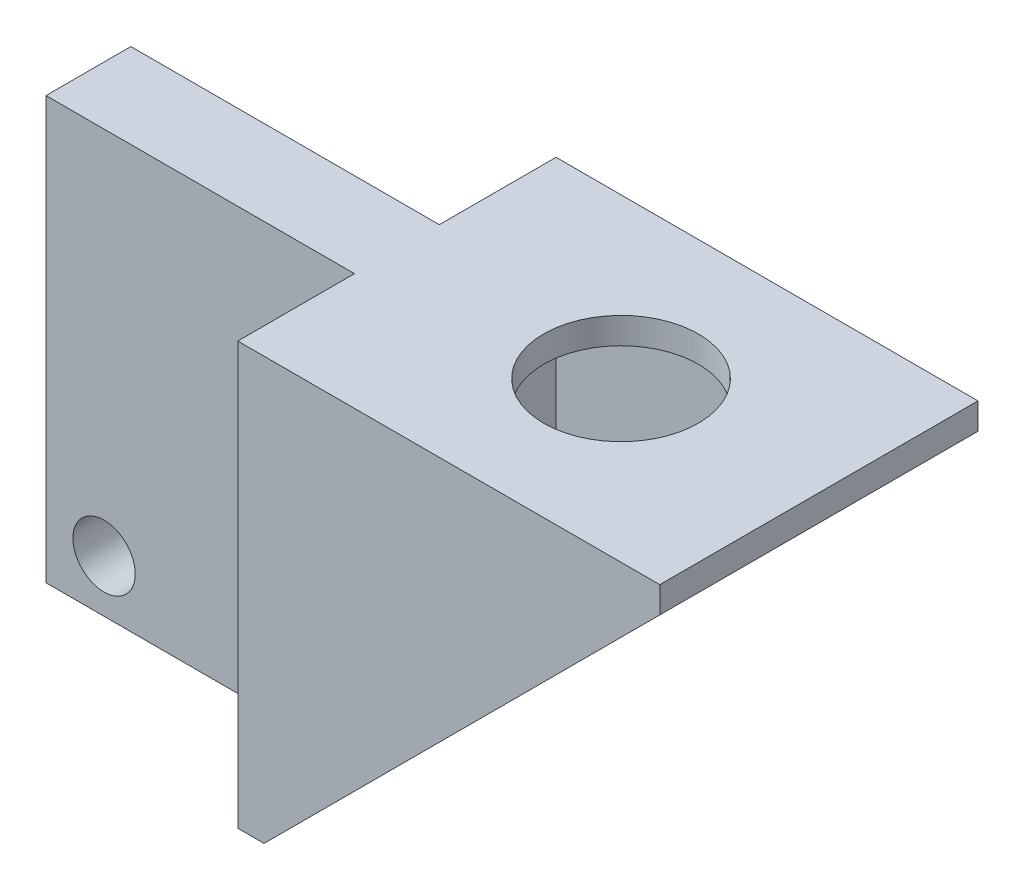
SolidWorks part; units mm, degrees
ref_plane "Front Plane" through (0, 0, 0) normal (0, 0, 1) x (1, 0, 0)
ref_plane "Top Plane" through (0, 0, 0) normal (0, 1, 0) x (1, 0, 0)
ref_plane "Right Plane" through (0, 0, 0) normal (1, 0, 0) x (0, 0, -1)
sketch "Sketch1" plane through (0, 0, 0) normal (0, 1, 0) x (1, 0, 0)
  line L0 (0, 0) -> (0, 24.003)
  line L1 (0, 24.003) -> (-29.845, 24.003)
  line L2 (-29.845, 24.003) -> (-29.845, 0)
  line L3 (-29.845, 0) -> (0, 0)
  circle A0 centre (-14.9225, 12.0015) radius 5.8357
  point P8 (-14.9225, 24.003)
  point P10 (-29.845, 12.0015)
  dimension "D3" = 11.6713
  dimension "D1" = 24.003
  dimension "D2" = 29.845
extrude "Boss-Extrude1" add sketch "Sketch1" along normal blind 1.9812
sketch "Sketch7" plane through (-29.845, 0, 0) normal (-1, 0, 0) x (0, 0, 1)
  line L4 (-24.003, 1.9812) -> (-24.003, -29.845)
  line L5 (-24.003, -29.845) -> (0, -29.845)
  line L6 (0, -29.845) -> (0, 1.9812)
  line L7 (0, 1.9812) -> (-24.003, 1.9812)
  dimension "D1" = 31.8262
extrude "Boss-Extrude4" add sketch "Sketch7" along normal blind 1.9812
sketch "Sketch8" plane through (0, 0, 0) normal (0, 0, 1) x (1, 0, 0)
  line L0 (-29.845, -29.845) -> (-29.845, 0)
  line L1 (-29.845, 0) -> (0, 0)
  line L2 (0, 0) -> (-29.845, -29.845)
extrude "Boss-Extrude5" add sketch "Sketch8" against normal blind 1.9812
sketch "Sketch9" plane through (0, 0, -24.003) normal (0, 0, -1) x (-1, 0, 0)
  line L0 (0, 0) -> (29.845, 0)
  line L1 (29.845, 0) -> (29.845, -29.845)
  line L2 (29.845, -29.845) -> (0, 0)
extrude "Boss-Extrude6" add sketch "Sketch9" against normal blind 1.9812
sketch "Sketch10" plane through (-31.8262, 0, 0) normal (-1, 0, 0) x (0, 0, 1)
  line L0 (-15.2015, -29.845) -> (-15.2015, 1.9812)
  line L1 (-24.003, -29.845) -> (0, -29.845) construction
  line L2 (-15.2015, 1.9812) -> (-8.8015, 1.9812)
  line L3 (-8.8015, 1.9812) -> (-8.8015, -29.845)
  line L4 (-8.8015, -29.845) -> (-15.2015, -29.845)
  line L5 (-12.0015, 1.9812) -> (-12.0015, -29.845) construction
  line L6 (0, 1.9812) -> (-24.003, 1.9812) construction
  point P10 (-12.0015, 1.9812)
  dimension "D1" = 31.8262
  dimension "D2" = 6.4
extrude "Boss-Extrude7" add sketch "Sketch10" along normal blind 23.2664
sketch "Sketch11" plane through (0, 0, -8.8015) normal (0, 0, 1) x (1, 0, 0)
  line L0 (-55.0926, -29.845) -> (-55.0926, -21.971)
  line L1 (-55.0926, -29.845) -> (-55.0926, 1.9812) construction
  line L2 (-55.0926, -21.971) -> (-31.8262, -21.971)
  line L3 (-31.8262, -29.845) -> (-31.8262, 1.9812) construction
  line L4 (-31.8262, -21.971) -> (-31.8262, -29.845)
  line L5 (-31.8262, -29.845) -> (-55.0926, -29.845)
  circle A0 centre (-50.7106, -25.908) radius 2.35
  circle A1 centre (-36.2606, -25.908) radius 2.35
  point P15 (-55.0926, -25.908)
  dimension "D1" = 4.7
  dimension "D2" = 4.7
  dimension "D3" = 7.874
  dimension "D4" = 14.45
  dimension "D5" = 4.382
extrude "Cut-Extrude1" cut sketch "Sketch11" against normal through all contours A0 | A1
equation "\"HoleD\"= 0.4595in"
equation "\"D3@Sketch1\"=\"HoleD\""
equation "\"BaseExtrude\"= 0.078in"
equation "\"BracketL\"= 0.945000in"
equation "\"D1@Sketch1\"=\"BracketL\""
equation "\"BracketW\"= 1.175000in"
equation "\"D2@Sketch1\"=\"BracketW\""
equation "\"D1@Boss-Extrude1\"=\"BaseExtrude\""
equation "\"D1@Sketch7\"=\"BracketW\"+\"BaseExtrude\""
equation "\"D1@Boss-Extrude4\"=\"BaseExtrude\""
equation "\"D1@Boss-Extrude5\"=\"BaseExtrude\""
equation "\"D1@Boss-Extrude6\"=\"BaseExtrude\""
equation "\"D1@Sketch10\"=\"BracketW\"+\"BaseExtrude\""
equation "\"LegoHoleD\"= 4.70mm"
equation "\"LegoHoleSpace\"= 9.75mm"
equation "\"D1@Sketch11\"=\"LegoHoleD\""
equation "\"D2@Sketch11\"=\"LegoHoleD\""
equation "\"D4@Sketch11\"=\"LegoHoleSpace\"+\"LegoHoleD\""
equation "\"D5@Sketch11\"= 0.08 + (1/2) * (\"LegoHoleD\")"
